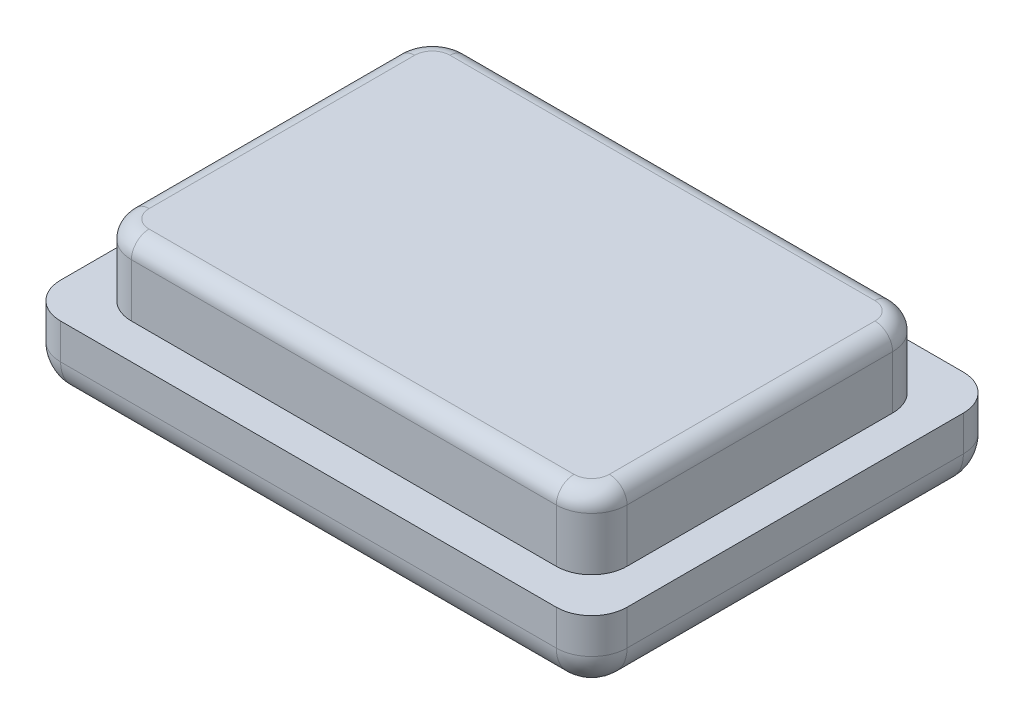
SolidWorks part; units mm, degrees
ref_plane "Alzado" through (0, 0, 0) normal (0, 0, 1) x (1, 0, 0)
ref_plane "Planta" through (0, 0, 0) normal (0, 1, 0) x (1, 0, 0)
ref_plane "Vista lateral" through (0, 0, 0) normal (1, 0, 0) x (0, 0, -1)
sketch "Croquis1" plane through (0, 0, 0) normal (0, 1, 0) x (1, 0, 0)
  line L1 (-6, -3.75) -> (6, -3.75) construction
  line L2 (-6, -3.75) -> (-6, 3.75) construction
  line L3 (-6, 3.75) -> (6, 3.75) construction
  line L4 (6, -3.75) -> (6, 3.75) construction
  line L5 (-6, -3.75) -> (6, 3.75) construction
  line L6 (-6, 3.75) -> (6, -3.75) construction
  line L7 (-7, -4.75) -> (7, -4.75) construction
  line L8 (-7, -4.75) -> (-7, 4.75) construction
  line L9 (-7, 4.75) -> (7, 4.75) construction
  line L10 (7, -4.75) -> (7, 4.75) construction
  line L11 (-7, -4.75) -> (7, 4.75) construction
  line L12 (-7, 4.75) -> (7, -4.75) construction
  line L13 (-8, -5.75) -> (8, -5.75)
  line L14 (-8, -5.75) -> (-8, 5.75)
  line L15 (-8, 5.75) -> (8, 5.75)
  line L16 (8, -5.75) -> (8, 5.75)
  line L17 (-8, -5.75) -> (8, 5.75) construction
  line L18 (-8, 5.75) -> (8, -5.75) construction
  point P0 (0, 0)
  point P6 (0, 0)
  point P11 (0, 0)
  dimension "D1" = 12
  dimension "D2" = 7.5
  dimension "D3" = 1
  dimension "D4" = 1
  dimension "D5" = 1
  dimension "D6" = 1
extrude "Saliente-Extruir2" add sketch "Croquis1" along normal blind 2 contours L15 L16 L13 L14
sketch "Croquis2" plane through (0, 2, 0) normal (0, 1, 0) x (1, 0, 0)
  line L0 (8, -5.75) -> (8, 5.75) construction
  line L1 (-7, -4.75) -> (7, -4.75)
  line L2 (-7, -4.75) -> (-7, 4.75)
  line L3 (-7, 4.75) -> (7, 4.75)
  line L4 (7, -4.75) -> (7, 4.75)
  line L5 (-7, -4.75) -> (7, 4.75) construction
  line L6 (-7, 4.75) -> (7, -4.75) construction
  line L7 (-8, 5.75) -> (8, 5.75) construction
  point P0 (0, 0)
  dimension "D1" = 1
  dimension "D2" = 1
extrude "Saliente-Extruir3" add sketch "Croquis2" along normal blind 2
fillet "Redondeo1" radius 1 8 edges at (8, 1, -5.75) (8, 1, 5.75) (-8, 1, 5.75) (-8, 1, -5.75) (8, 0, 0) (0, 0, -5.75) (-8, 0, 0) (0, 0, 5.75)
fillet "Redondeo2" radius 1 4 edges at (7, 3, 4.75) (7, 3, -4.75) (-7, 3, -4.75) (-7, 3, 4.75)
fillet "Redondeo3" radius 0.5 8 edges at (6.7071, 4, -4.4571) (7, 4, 0) (6.7071, 4, 4.4571) (0, 4, 4.75) (-6.7071, 4, 4.4571) (-7, 4, 0) (-6.7071, 4, -4.4571) (0, 4, -4.75)
equation "\"D4@Croquis1\"=\"D3@Croquis1\""
equation "\"D6@Croquis1\"=\"D3@Croquis1\""
equation "\"D5@Croquis1\"=\"D3@Croquis1\""
equation "\"D1@Croquis2\"=\"D3@Croquis1\""
equation "\"D2@Croquis2\"=\"D3@Croquis1\""
